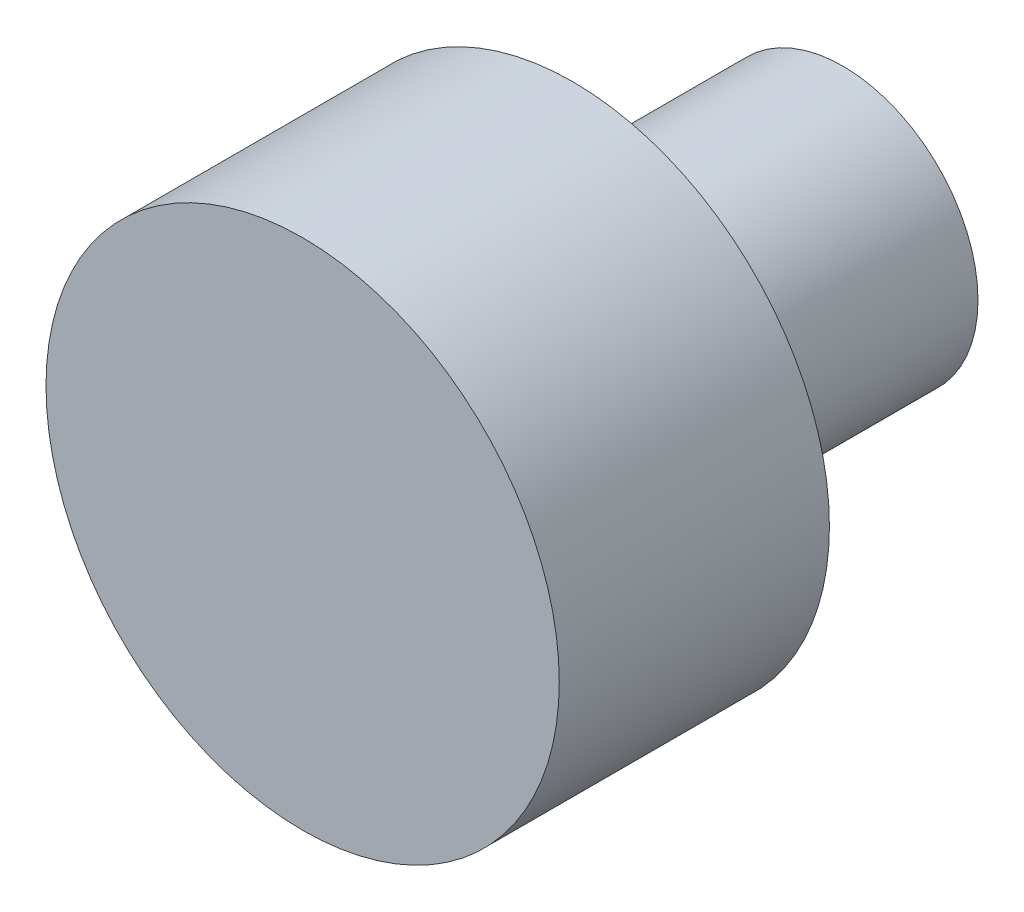
SolidWorks part; units mm, degrees
material "AISI 4340 Steel, normalized"
ref_plane "Front Plane" through (0, 0, 0) normal (0, 0, 1) x (1, 0, 0)
ref_plane "Top Plane" through (0, 0, 0) normal (0, 1, 0) x (1, 0, 0)
ref_plane "Right Plane" through (0, 0, 0) normal (1, 0, 0) x (0, 0, -1)
sketch "Sketch1" plane through (0, 0, 0) normal (0, 0, 1) x (1, 0, 0)
  circle A0 centre (0, 0) radius 1
extrude "Thread_Envelope" add sketch "Sketch1" along normal blind 2 from offset 2
sketch "Sketch2" plane through (0, 0, 0) normal (0, 0, 1) x (1, 0, 0)
  circle A0 centre (0, 0) radius 1.9
extrude "Head_Envelope" add sketch "Sketch2" along normal blind 2
